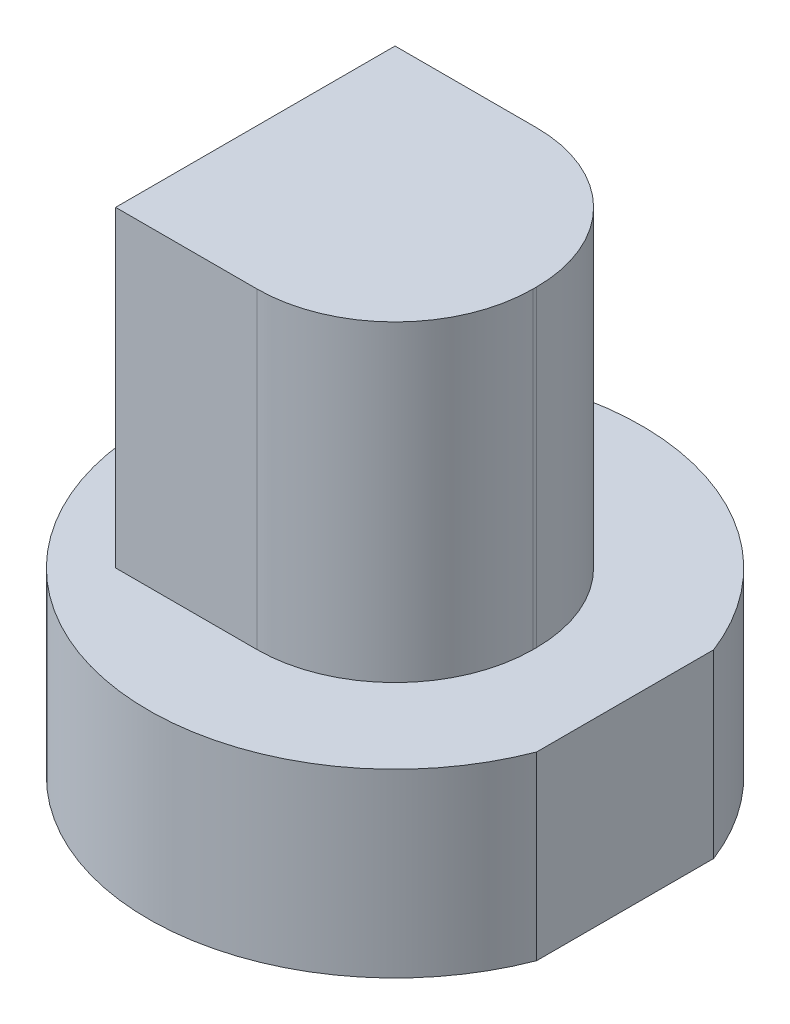
SolidWorks part; units mm, degrees
ref_plane "Alzado" through (0, 0, 0) normal (0, 0, 1) x (1, 0, 0)
ref_plane "Planta" through (0, 0, 0) normal (0, 1, 0) x (1, 0, 0)
ref_plane "Vista lateral" through (0, 0, 0) normal (1, 0, 0) x (0, 0, -1)
sketch "Croquis1" plane through (0, 0, 0) normal (0, 1, 0) x (1, 0, 0)
  line L0 (0, 7.5) -> (0, -7.5) construction
  line L1 (7, 2.6926) -> (7, -2.6926)
  arc A0 (7, 2.6926) -> (7, -2.6926) centre (0, 0) ccw
  dimension "D1" = 15
  dimension "D2" = 7
extrude "Saliente-Extruir1" add sketch "Croquis1" along normal blind 5.5
sketch "Croquis2" plane through (0, 5.5, 0) normal (0, 1, 0) x (1, 0, 0)
  line L1 (-4.25, -4.25) -> (0.05, -4.25)
  line L2 (-4.25, -4.25) -> (-4.25, 4.25)
  line L3 (-4.25, 4.25) -> (0.05, 4.25)
  line L4 (4.25, -0.05) -> (4.25, 0.05)
  line L5 (-4.25, -4.25) -> (4.25, 4.25) construction
  line L6 (-4.25, 4.25) -> (4.25, -4.25) construction
  arc A0 (0.05, 4.25) -> (4.25, 0.05) centre (0.05, 0.05) cw
  arc A1 (0.05, -4.25) -> (4.25, -0.05) centre (0.05, -0.05) ccw
  point P0 (0, 0)
  dimension "D3" = 4.2
  dimension "D1" = 8.5
  dimension "D2" = 8.5
extrude "Saliente-Extruir2" add sketch "Croquis2" along normal blind 9.5
sketch "Croquis3" plane through (0, 0, 0) normal (0, -1, 0) x (1, 0, 0)
  circle A0 centre (0, 0) radius 3.75
  dimension "D1" = 7.5
extrude "Cortar-Extruir1" cut sketch "Croquis3" against normal blind 1.2
sketch "Croquis5" plane through (0, 1.2, 0) normal (0, -1, 0) x (1, 0, 0)
  circle A0 centre (0, 0) radius 2.75
  dimension "D1" = 5.5
extrude "Cortar-Extruir3" cut sketch "Croquis5" against normal blind 13
